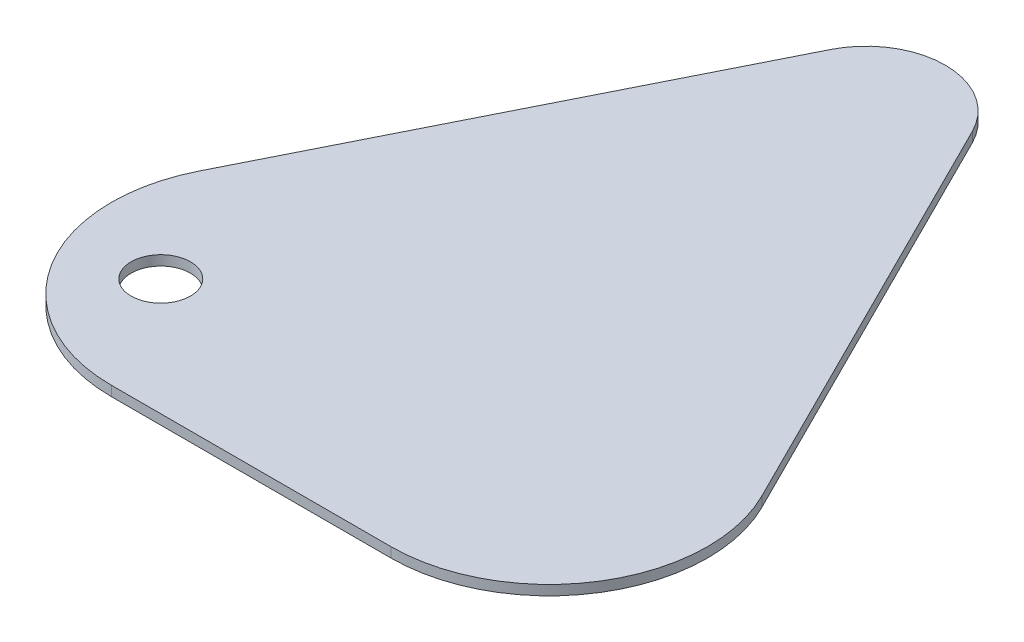
SolidWorks part; units mm, degrees
material "Nylon 101"
ref_plane "Front Plane" through (0, 0, 0) normal (0, 0, 1) x (1, 0, 0)
ref_plane "Top Plane" through (0, 0, 0) normal (0, 1, 0) x (1, 0, 0)
ref_plane "Right Plane" through (0, 0, 0) normal (1, 0, 0) x (0, 0, -1)
sketch "Sketch1" plane through (0, 0, 0) normal (0, 1, 0) x (1, 0, 0)
  line L1 (0, 0) -> (7.0557, 0)
  line L2 (14.2111, 11.5777) -> (3.5777, 32.8446)
  line L3 (0, 0) -> (-7.0557, 0)
  line L4 (-14.2111, 11.5777) -> (-3.5777, 32.8446)
  arc A0 (3.5777, 32.8446) -> (-3.5777, 32.8446) centre (0, 31.0557) ccw
  arc A1 (7.0557, 0) -> (14.2111, 11.5777) centre (7.0557, 8) ccw
  arc A2 (-7.0557, 0) -> (-14.2111, 11.5777) centre (-7.0557, 8) cw
  circle A3 centre (-10.4583, 5.8971) radius 1.5
  point P7 (0, 40)
  point P10 (20, 0)
  point P13 (-20, 0)
  dimension "D4" = 4
  dimension "D5" = 8
  dimension "D6" = 3
  dimension "D1" = 20
  dimension "D2" = 20
  dimension "D3" = 40
extrude "Boss-Extrude1" add sketch "Sketch1" along normal mid plane 0.5
